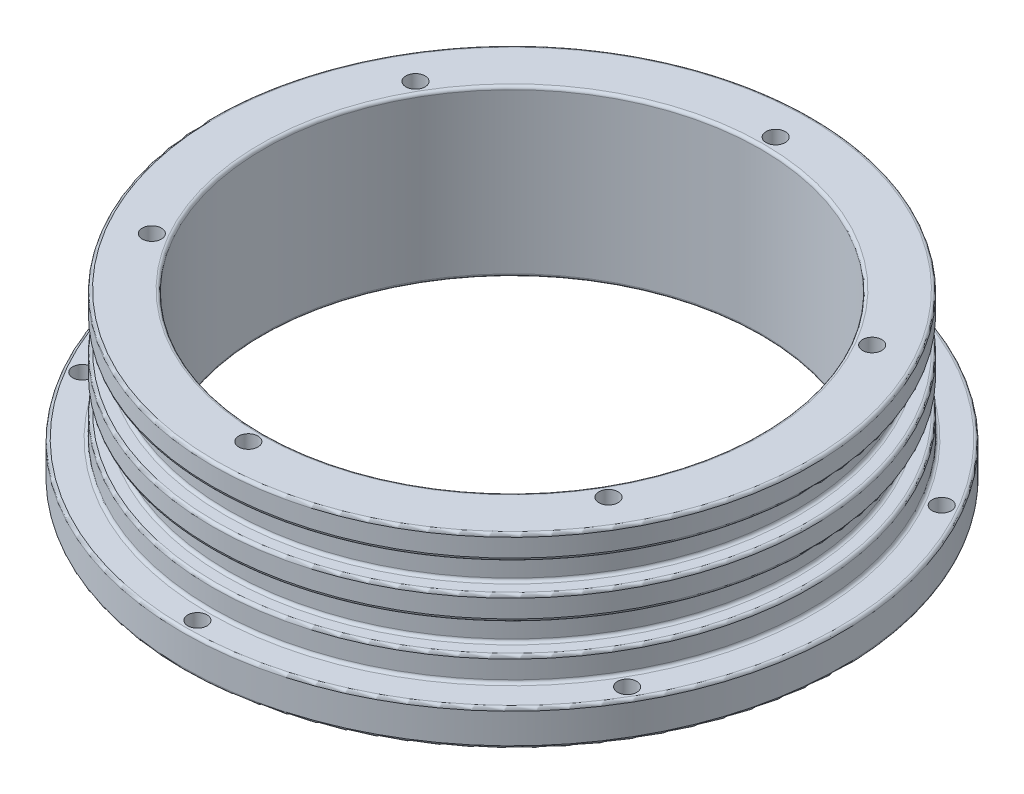
SolidWorks part; units mm, degrees
ref_plane "Front Plane" through (0, 0, 0) normal (0, 0, 1) x (1, 0, 0)
ref_plane "Top Plane" through (0, 0, 0) normal (0, 1, 0) x (1, 0, 0)
ref_plane "Right Plane" through (0, 0, 0) normal (1, 0, 0) x (0, 0, -1)
sketch "Sketch1" plane through (0, 0, 0) normal (0, 1, 0) x (1, 0, 0)
  circle A0 centre (0, 0) radius 55
  circle A1 centre (0, 0) radius 52.5 construction
  circle A2 centre (0, 52.5) radius 1.6
  circle A3 centre (45.4663, 26.25) radius 1.6
  circle A4 centre (45.4663, -26.25) radius 1.6
  circle A5 centre (0, -52.5) radius 1.6
  circle A6 centre (-45.4663, -26.25) radius 1.6
  circle A7 centre (-45.4663, 26.25) radius 1.6
  point P22 (0, 0)
  dimension "D1" = 110
  dimension "D2" = 105
  dimension "D3" = 3.2
  dimension "D4" = 6
extrude "Boss-Extrude1" add sketch "Sketch1" along normal blind 6
sketch "Sketch2" plane through (0, 6, 0) normal (0, 1, 0) x (1, 0, 0)
  circle A0 centre (0, 0) radius 50
  dimension "D1" = 100
extrude "Boss-Extrude2" add sketch "Sketch2" along normal blind 21.6
sketch "Sketch3" plane through (0, 27.6, 0) normal (0, 1, 0) x (1, 0, 0)
  circle A0 centre (0, 0) radius 41.5
  point P7 (0, 0)
  point P8 (0, 0)
  point P22 (0, 0)
  dimension "D1" = 83
extrude "Cut-Extrude1" cut sketch "Sketch3" against normal through all
sketch "Sketch5" plane through (0, 27.6, 0) normal (0, 1, 0) x (1, 0, 0)
  circle A0 centre (0, 0) radius 44 construction
  circle A1 centre (0, 44) radius 1.6
  circle A2 centre (38.1051, 22) radius 1.6
  circle A3 centre (38.1051, -22) radius 1.6
  circle A4 centre (0, -44) radius 1.6
  circle A5 centre (-38.1051, -22) radius 1.6
  circle A6 centre (-38.1051, 22) radius 1.6
  point P6 (0, 0)
  point P21 (0, 0)
  dimension "D1" = 88
  dimension "D2" = 3.2
  dimension "D3" = 6
extrude "Cut-Extrude2" cut sketch "Sketch5" against normal blind 5
sketch "Sketch6" plane through (0, 0, 0) normal (0, -1, 0) x (1, 0, 0)
  circle A0 centre (0, 0) radius 46
  circle A1 centre (0, 0) radius 50
  dimension "D1" = 100
  dimension "D2" = 92
extrude "Cut-Extrude3" cut sketch "Sketch6" against normal blind 2.7
sketch "Sketch7" plane through (0, 0, 0) normal (1, 0, 0) x (0, 0, -1)
  line L0 (0, 0) -> (0, 27.6) construction
  line L2 (-50, 27.6) -> (-50, 6) construction
  line L3 (-50, 23.6) -> (-47.3, 23.6)
  line L4 (-50, 23.6) -> (-50, 18.8)
  line L5 (-50, 18.8) -> (-47.3, 18.8)
  line L6 (-47.3, 23.6) -> (-47.3, 18.8)
  line L7 (-50, 14.8) -> (-47.3, 14.8)
  line L8 (-50, 14.8) -> (-50, 10)
  line L9 (-50, 10) -> (-47.3, 10)
  line L10 (-47.3, 14.8) -> (-47.3, 10)
  line L11 (50, 27.6) -> (-50, 27.6) construction
  point P2 (0, 0)
  point P3 (0, 0)
  point P4 (0, 0)
  point P17 (0, 0)
  dimension "D1" = 8.8
  dimension "D2" = 17.6
  dimension "D3" = 4.8
  dimension "D4" = 2.7
revolve "Cut-Revolve1" cut sketch "Sketch7" angle 360 about L0
fillet "Fillet1" radius 0.5 18 edges at (0, 27.6, 50) (0, 18.8, -47.3) (0, 18.8, -50) (0, 23.6, -50) (0, 23.6, -47.3) (0, 14.8, -47.3) (0, 10, -47.3) (0, 14.8, -50) (0, 10, -50) (0, 6, 50) (0, 2.7, -46) (0, 2.7, -50) (0, 27.6, 41.5) (0, 0, 41.5) (0, 0, -46) (0, 0, -50) (0, 6, 55) (0, 0, 55)
